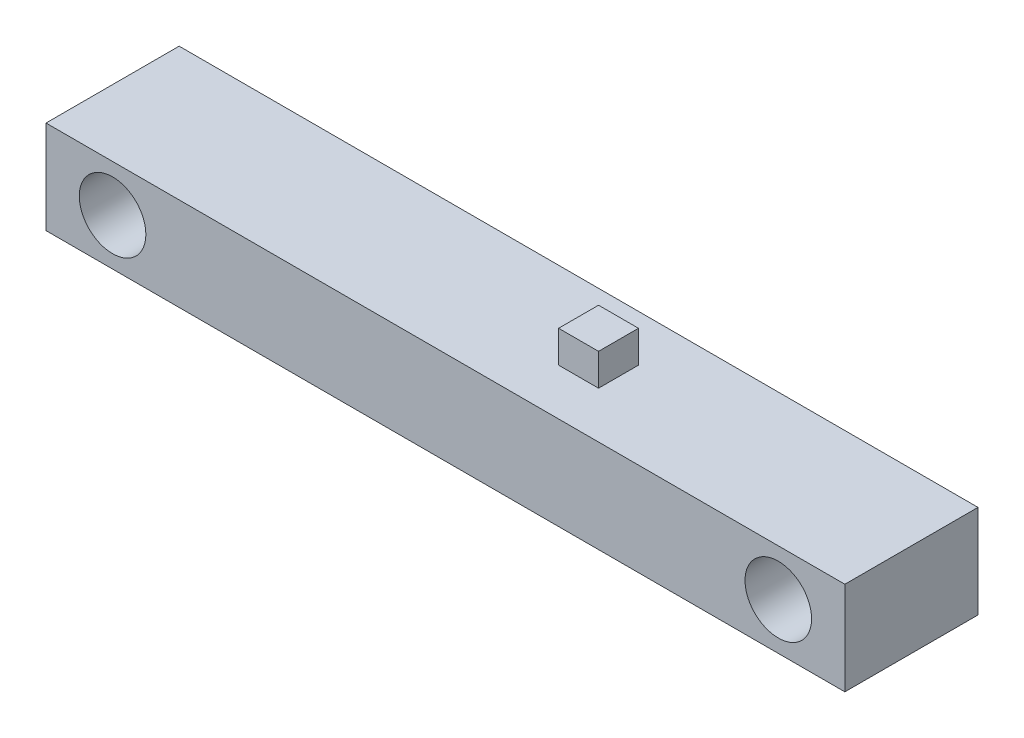
SolidWorks part; units mm, degrees
ref_plane "Front Plane" through (0, 0, 0) normal (0, 0, 1) x (1, 0, 0)
ref_plane "Top Plane" through (0, 0, 0) normal (0, 1, 0) x (1, 0, 0)
ref_plane "Right Plane" through (0, 0, 0) normal (1, 0, 0) x (0, 0, -1)
sketch "Sketch1" plane through (0, 0, 0) normal (0, 1, 0) x (1, 0, 0)
  line L1 (-150, 50) -> (150, 50)
  line L2 (-150, 50) -> (-150, 0)
  line L3 (-150, 0) -> (150, 0)
  line L4 (150, 50) -> (150, 0)
  dimension "D1" = 300
  dimension "D2" = 50
extrude "Boss-Extrude1" add sketch "Sketch1" along normal blind 35
sketch "Sketch2" plane through (0, 35, 0) normal (0, 1, 0) x (1, 0, 0)
  line L0 (150, 50) -> (-150, 50) construction
  line L1 (25, 32.5) -> (40, 32.5)
  line L2 (25, 32.5) -> (25, 17.5)
  line L3 (25, 17.5) -> (40, 17.5)
  line L4 (40, 32.5) -> (40, 17.5)
  line L6 (-150, 50) -> (-150, 0) construction
  dimension "D1" = 15
  dimension "D2" = 15
  dimension "D3" = 17.5
  dimension "D4" = 175
extrude "Boss-Extrude2" add sketch "Sketch2" along normal blind 12
sketch "Sketch3" plane through (0, 0, 0) normal (0, 0, 1) x (1, 0, 0)
  line L3 (-150, 35) -> (150, 35) construction
  circle A1 centre (-125, 17.5) radius 12.5
  circle A2 centre (125, 17.5) radius 12.5
  dimension "D2" = 250
  dimension "D1" = 25
  dimension "D5" = 25
  dimension "D3" = 125
  dimension "D4" = 17.5
extrude "Cut-Extrude1" cut sketch "Sketch3" against normal up to next
